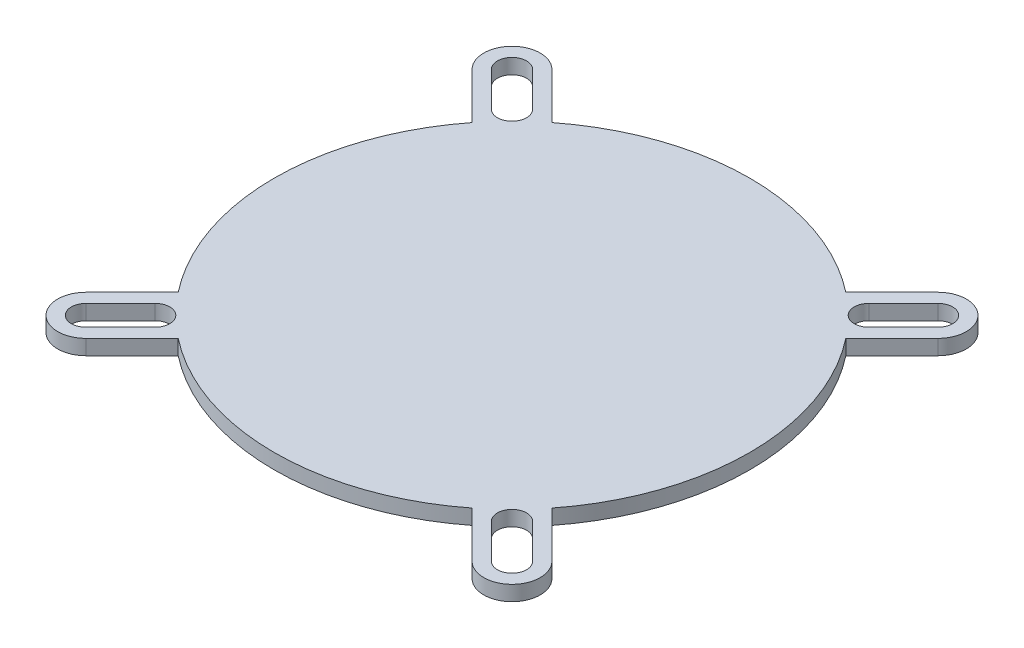
SolidWorks part; units mm, degrees
ref_plane "前视基准面" through (0, 0, 0) normal (0, 0, 1) x (1, 0, 0)
ref_plane "上视基准面" through (0, 0, 0) normal (0, 1, 0) x (1, 0, 0)
ref_plane "右视基准面" through (0, 0, 0) normal (1, 0, 0) x (0, 0, -1)
sketch "草图1" plane through (0, 0, 0) normal (0, 1, 0) x (1, 0, 0)
  line L0 (-17.8544, 17.8544) -> (17.8544, -17.8544) construction
  line L1 (0, 0) -> (25.25, 0) construction
  line L2 (-17.8544, -17.8544) -> (17.8544, 17.8544) construction
  circle A0 centre (0, 0) radius 25.25
  dimension "D1" = 50.5
  dimension "D2" = 45
extrude "凸台-拉伸1" add sketch "草图1" along normal blind 1.6
sketch "草图2" plane through (0, 1.6, 0) normal (0, 1, 0) x (1, 0, 0)
  line L0 (-22.6274, 22.6274) -> (0, 0) construction
  line L1 (-20.5061, 24.7487) -> (0, 4.2426)
  line L2 (-24.7487, 20.5061) -> (-4.2426, 0)
  line L3 (-17.8544, 17.8544) -> (17.8544, -17.8544) construction
  line L4 (-22.6274, -22.6274) -> (22.6274, 22.6274) construction
  line L5 (-24.7487, -20.5061) -> (-4.2426, 0)
  line L6 (-20.5061, -24.7487) -> (0, -4.2426)
  line L7 (0, 4.2426) -> (20.5061, 24.7487)
  line L8 (0, -4.2426) -> (20.5061, -24.7487)
  line L9 (4.2426, 0) -> (24.7487, -20.5061)
  line L10 (2.1213, -2.1213) -> (22.6274, -22.6274) construction
  line L11 (4.2426, 0) -> (24.7487, 20.5061)
  line L12 (-22.6274, 22.6274) -> (-18.9505, 18.9505) construction
  line L13 (-21.5314, 23.7234) -> (-17.8544, 20.0465)
  line L14 (-23.7234, 21.5314) -> (-20.0465, 17.8544)
  line L15 (22.6274, 22.6274) -> (18.9505, 18.9505) construction
  line L16 (23.7234, 21.5314) -> (20.0465, 17.8544)
  line L17 (21.5314, 23.7234) -> (17.8544, 20.0465)
  line L18 (22.6274, -22.6274) -> (18.9505, -18.9505) construction
  line L19 (21.5314, -23.7234) -> (17.8544, -20.0465)
  line L20 (23.7234, -21.5314) -> (20.0465, -17.8544)
  line L21 (-22.6274, -22.6274) -> (-18.9505, -18.9505) construction
  line L22 (-23.7234, -21.5314) -> (-20.0465, -17.8544)
  line L23 (-21.5314, -23.7234) -> (-17.8544, -20.0465)
  arc A0 (-20.5061, 24.7487) -> (-24.7487, 20.5061) centre (-22.6274, 22.6274) ccw
  arc A1 (20.5061, -24.7487) -> (24.7487, -20.5061) centre (22.6274, -22.6274) ccw
  arc A2 (-24.7487, -20.5061) -> (-20.5061, -24.7487) centre (-22.6274, -22.6274) ccw
  arc A3 (24.7487, 20.5061) -> (20.5061, 24.7487) centre (22.6274, 22.6274) ccw
  arc A4 (-21.5314, 23.7234) -> (-23.7234, 21.5314) centre (-22.6274, 22.6274) ccw
  arc A5 (-20.0465, 17.8544) -> (-17.8544, 20.0465) centre (-18.9505, 18.9505) ccw
  circle A6 centre (0, 0) radius 25.25 construction
  arc A7 (23.7234, 21.5314) -> (21.5314, 23.7234) centre (22.6274, 22.6274) ccw
  arc A8 (17.8544, 20.0465) -> (20.0465, 17.8544) centre (18.9505, 18.9505) ccw
  arc A9 (21.5314, -23.7234) -> (23.7234, -21.5314) centre (22.6274, -22.6274) ccw
  arc A10 (20.0465, -17.8544) -> (17.8544, -20.0465) centre (18.9505, -18.9505) ccw
  arc A11 (-23.7234, -21.5314) -> (-21.5314, -23.7234) centre (-22.6274, -22.6274) ccw
  arc A12 (-17.8544, -20.0465) -> (-20.0465, -17.8544) centre (-18.9505, -18.9505) ccw
  point P2 (0, 0)
  point P9 (0, 0)
  point P17 (-20.7889, 20.7889)
  point P33 (20.7889, 20.7889)
  point P42 (20.7889, -20.7889)
  point P49 (-20.7889, -20.7889)
  point P55 (0, 0)
  dimension "D1" = 3
  dimension "D3" = 1.55
  dimension "D2" = 64
  dimension "D4" = 4
extrude "凸台-拉伸2" add sketch "草图2" against normal blind 1.6
